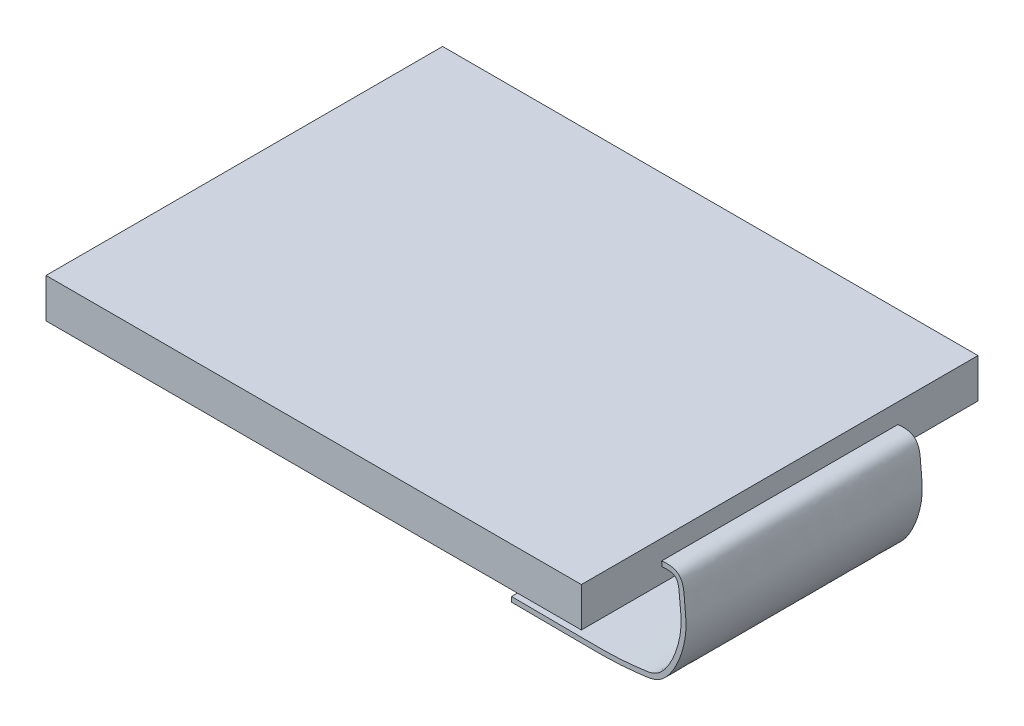
SolidWorks part; units mm, degrees
ref_plane "Front Plane" through (0, 0, 0) normal (0, 0, 1) x (1, 0, 0)
ref_plane "Top Plane" through (0, 0, 0) normal (0, 1, 0) x (1, 0, 0)
ref_plane "Right Plane" through (0, 0, 0) normal (1, 0, 0) x (0, 0, -1)
sketch "Sketch1" plane through (0, 0, 0) normal (0, 1, 0) x (1, 0, 0)
  line L0 (0, 34.2606) -> (0, -38.8098) construction
  line L1 (-61.0341, 0) -> (57.1484, 0) construction
  line L3 (-27.2, 20.15) -> (27.2, 20.15)
  line L4 (-27.2, 20.15) -> (-27.2, -20.15)
  line L5 (-27.2, -20.15) -> (27.2, -20.15)
  line L6 (27.2, 20.15) -> (27.2, -20.15)
  dimension "D1" = 54.4
  dimension "D2" = 40.3
extrude "Boss-Extrude1" add sketch "Sketch1" along normal blind 4
sketch "Sketch2" plane through (0, 0, 0) normal (0, 0, 1) x (1, 0, 0)
  line L0 (27.2, 4) -> (27.2, 0) construction
  line L1 (27.2, 2) -> (27.2654, 1.5043)
  line L2 (11.9494, -8.7517) -> (11.9494, -9.2517)
  spline S0 degree 3 poles (27.2, 2) (29.5639, 2.312) (29.4028, 0.2634) (29.9791, -3.9574) (28.0367, -8.6665) (21.5829, -9.5112) (20.5346, -9.2517) (11.9494, -9.2517) knots 0 0 0 0 0.127112 0.164895 0.354175 0.440051 1 1 1 1
  spline S1 degree 1 poles (27.2654, 1.5043) (11.9494, -8.7517) knots 0 0 1 1 construction
  spline S2 degree 3 poles (27.2654, 1.5043) (27.3862, 1.5202) (27.645, 1.5436) (28.0371, 1.5373) (28.3864, 1.4576) (28.6123, 1.311) (28.774, 1.1028) (28.9006, 0.7717) (29.0079, 0.1857) (29.0505, -0.761) (29.1945, -1.8946) (29.1866, -2.9723) (28.996, -4.1416) (28.5484, -5.6605) (27.8605, -7.004) (27.0816, -7.8895) (26.5292, -8.2482) (25.944, -8.4307) (25.3088, -8.515) (24.6785, -8.5861) (23.9175, -8.6651) (23.0479, -8.7362) (22.0555, -8.7858) (21.0178, -8.8071) (19.8447, -8.8074) (18.448, -8.7942) (17.0254, -8.7782) (15.6881, -8.7661) (14.5756, -8.7585) (13.5446, -8.754) (12.6595, -8.7521) (12.1833, -8.7517) (11.9494, -8.7517) knots 0 0 0 0 0.007812 0.015625 0.03125 0.046875 0.0625 0.078125 0.09375 0.125 0.15625 0.1875 0.21875 0.25 0.3125 0.34375 0.375 0.40625 0.4375 0.46875 0.5 0.5625 0.625 0.6875 0.75 0.8125 0.875 0.90625 0.9375 0.96875 0.984375 1 1 1 1
  dimension "D1" = 0.5
extrude "Boss-Extrude2" add sketch "Sketch2" along normal blind 12 and the other way blind 12 separate body
